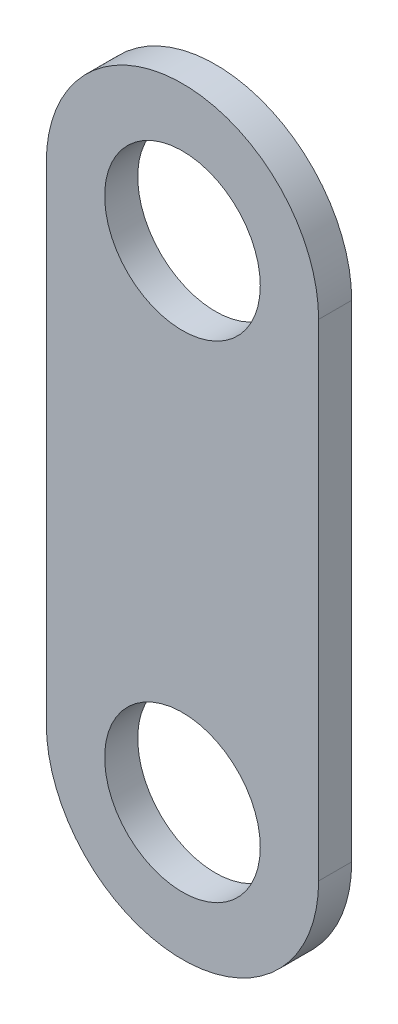
SolidWorks part; units mm, degrees
ref_plane "Alzado" through (0, 0, 0) normal (0, 0, 1) x (1, 0, 0)
ref_plane "Planta" through (0, 0, 0) normal (0, 1, 0) x (1, 0, 0)
ref_plane "Vista lateral" through (0, 0, 0) normal (1, 0, 0) x (0, 0, -1)
sketch "Croquis1" plane through (0, 0, 0) normal (0, 0, 1) x (1, 0, 0)
  line L0 (0, 0) -> (0, 25) construction
  line L1 (-7, 25) -> (-7, 0)
  line L2 (7, 25) -> (7, 0)
  arc A0 (-7, 0) -> (7, 0) centre (0, 0) ccw
  arc A1 (7, 25) -> (-7, 25) centre (0, 25) ccw
  circle A2 centre (0, 0) radius 4
  arc A3 (4, 25) -> (-4, 25) centre (0, 25) ccw
  arc A5 (4, 25) -> (-4, 25) centre (0, 25) cw
  dimension "D1" = 14
  dimension "D2" = 14
  dimension "D4" = 8
  dimension "D5" = 4
  dimension "D3" = 25
extrude "Saliente-Extruir1" add sketch "Croquis1" along normal blind 1.7
